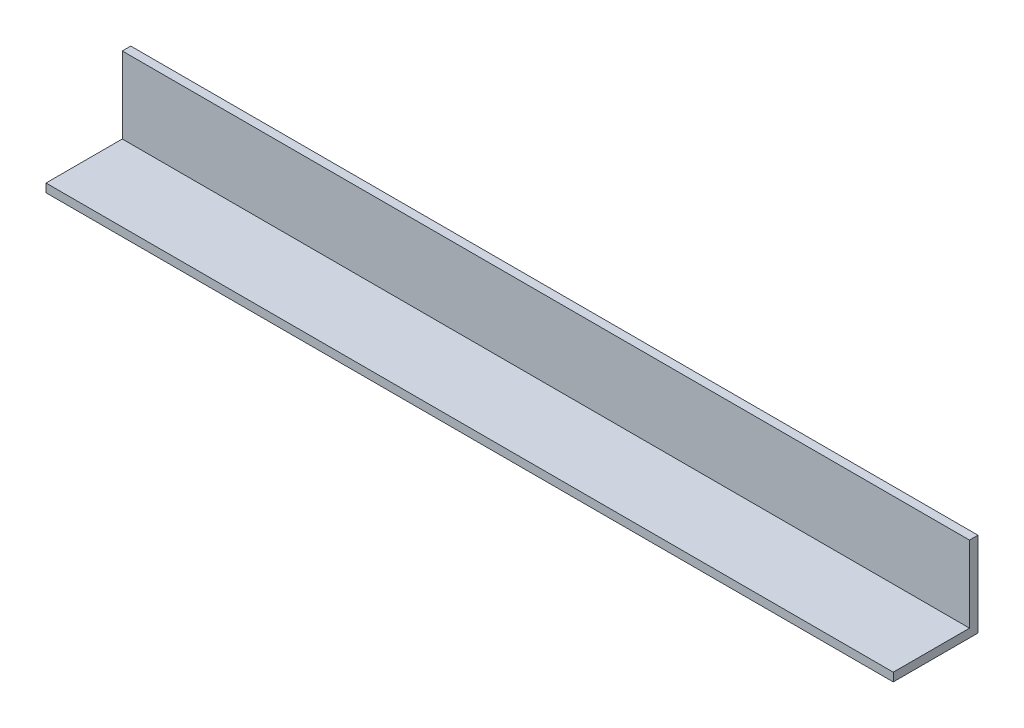
SolidWorks part; units mm, degrees
ref_plane "Alzado" through (0, 0, 0) normal (0, 0, 1) x (1, 0, 0)
ref_plane "Planta" through (0, 0, 0) normal (0, 1, 0) x (1, 0, 0)
ref_plane "Vista lateral" through (0, 0, 0) normal (1, 0, 0) x (0, 0, -1)
sketch "Croquis1" plane through (0, 0, 0) normal (1, 0, 0) x (0, 0, -1)
  line L1 (0, 0) -> (-15, 0)
  line L3 (-1.5, 1.5) -> (-15, 1.5)
  line L4 (-15, 0) -> (-15, 1.5)
  line L6 (0, 0) -> (0, 15)
  line L7 (0, 15) -> (-1.5, 15)
  line L8 (-1.5, 1.5) -> (-1.5, 15)
  dimension "D1" = 15
  dimension "D2" = 1.5
  dimension "D3" = 15
  dimension "D4" = 1.5
extrude "Saliente-Extruir1" add sketch "Croquis1" along normal blind 150
